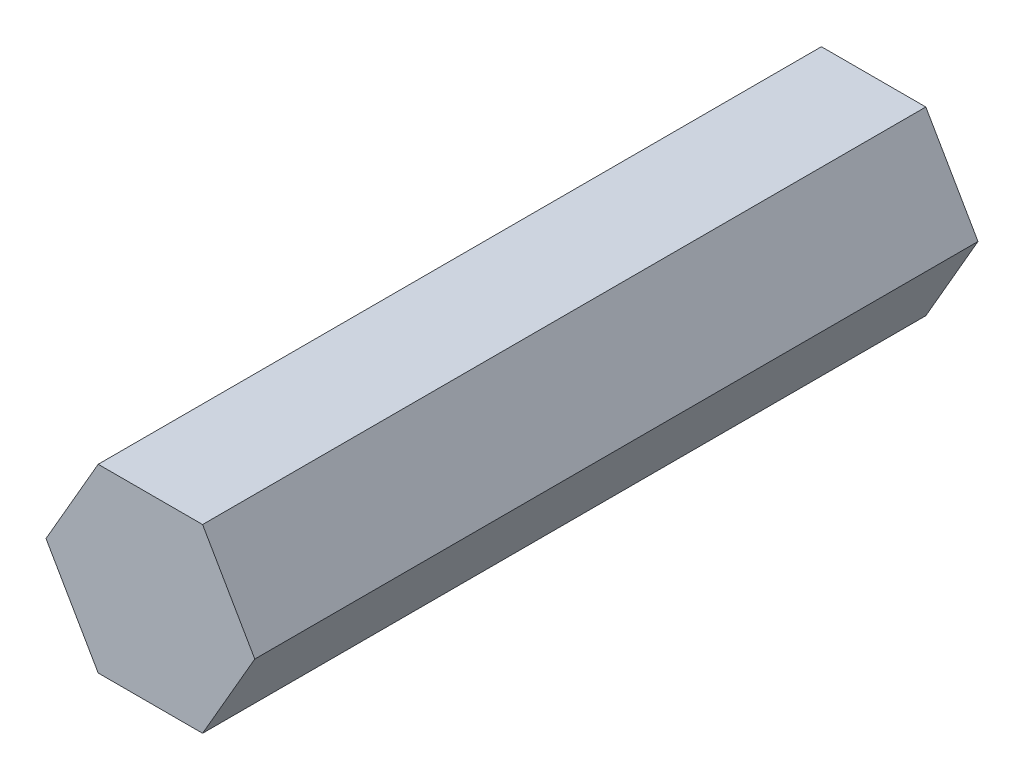
SolidWorks part; units mm, degrees
material "1060 Alloy"
ref_plane "Front Plane" through (0, 0, 0) normal (0, 0, 1) x (1, 0, 0)
ref_plane "Top Plane" through (0, 0, 0) normal (0, 1, 0) x (1, 0, 0)
ref_plane "Right Plane" through (0, 0, 0) normal (1, 0, 0) x (0, 0, -1)
sketch "Sketch1" plane through (0, 0, 0) normal (0, 0, 1) x (1, 0, 0)
  line L1 (7.3323, 0) -> (3.6662, 6.35)
  line L2 (3.6662, 6.35) -> (-3.6662, 6.35)
  line L3 (-3.6662, 6.35) -> (-7.3323, 0)
  line L4 (-7.3323, 0) -> (-3.6662, -6.35)
  line L5 (-3.6662, -6.35) -> (3.6662, -6.35)
  line L6 (3.6662, -6.35) -> (7.3323, 0)
  circle A0 centre (0, 0) radius 6.35 construction
  dimension "D1" = 12.7
extrude "Boss-Extrude1" add sketch "Sketch1" along normal blind 50.8
